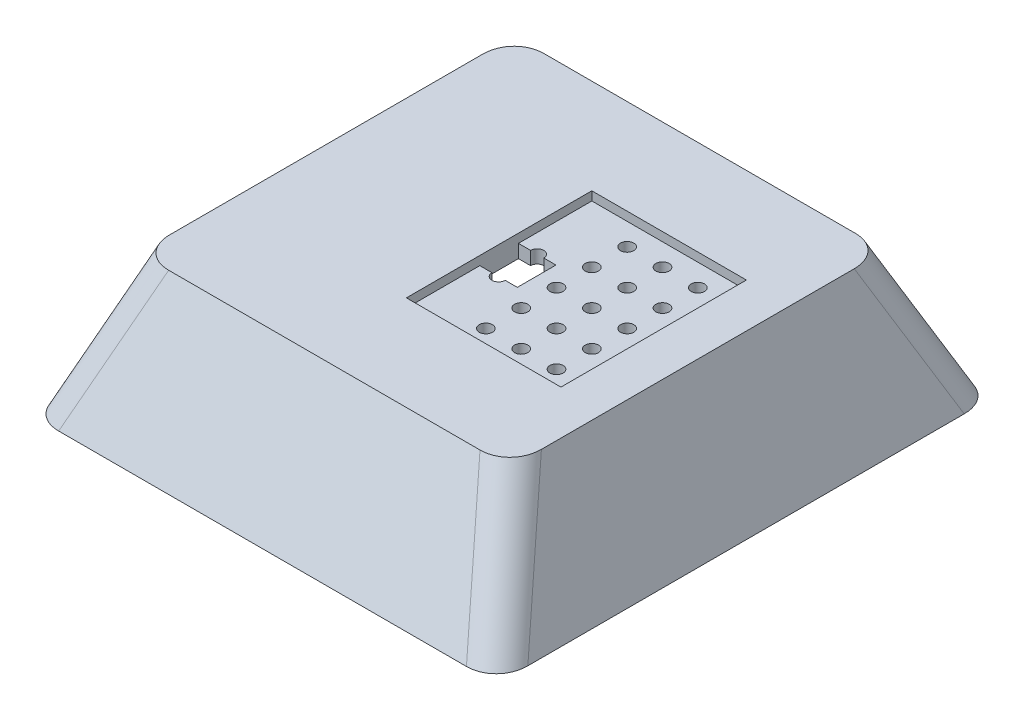
SolidWorks part; units mm, degrees
ref_plane "Front Plane" through (0, 0, 0) normal (0, 0, 1) x (1, 0, 0)
ref_plane "Top Plane" through (0, 0, 0) normal (0, 1, 0) x (1, 0, 0)
ref_plane "Right Plane" through (0, 0, 0) normal (1, 0, 0) x (0, 0, -1)
sketch "Master_Geometry" plane through (0, 0, 0) normal (0, 0, 1) x (1, 0, 0)
  line L0 (-48, -3.5) -> (-53, -3.5)
  line L1 (-47.5, -3.5) -> (47.5, -3.5) construction
  line L2 (-47.5, -3.5) -> (-47.5, 3.5) construction
  line L3 (-47.5, 3.5) -> (47.5, 3.5) construction
  line L4 (47.5, -3.5) -> (47.5, 3.5) construction
  line L5 (-47.5, -3.5) -> (47.5, 3.5) construction
  line L6 (-47.5, 3.5) -> (47.5, -3.5) construction
  line L7 (-53, -3.5) -> (-42.0809, 26.5)
  line L8 (-42.0809, 26.5) -> (42.0809, 26.5)
  line L13 (42.0809, 26.5) -> (53, -3.5)
  line L14 (53, -3.5) -> (48, -3.5)
  line L15 (48, -3.5) -> (48, 4)
  line L16 (48, 4) -> (38, 4)
  line L17 (38, 4) -> (38, 21.5)
  line L18 (38, 21.5) -> (-38, 21.5)
  line L19 (-38, 21.5) -> (-38, 4)
  line L20 (-38, 4) -> (-48, 4)
  line L21 (-48, 4) -> (-48, -3.5)
  point P0 (0, 0)
  dimension "D1" = 95
  dimension "D2" = 7
  dimension "D3" = 18
  dimension "D4" = 0.5
  dimension "D5" = 0.5
  dimension "D6" = 10
  dimension "D7" = 0.5
  dimension "D8" = 0.5
  dimension "D9" = 10
  dimension "D11" = 70
  dimension "D12" = 70
  dimension "D19" = 5
  dimension "D20" = 5
  dimension "D10" = 5
extrude "Top_Enclosure" add sketch "Master_Geometry" along normal blind 65
sketch "Sketch2" plane through (0, 0, 65) normal (0, 0, 1) x (1, 0, 0)
  line L0 (-42.0809, 26.5) -> (42.0809, 26.5)
  line L1 (42.0809, 26.5) -> (53, -3.5)
  line L2 (53, -3.5) -> (-53, -3.5)
  line L3 (-53, -3.5) -> (-42.0809, 26.5)
extrude "Top_Extra" add sketch "Sketch2" along normal blind 10
ref_plane "Plane_Symm" through (0, 0, 32.5) normal (0, 0, -1) x (-1, 0, 0)
mirror "Mirror1" about plane through (0, 0, 32.5) normal (0, 0, -1) of "Top_Extra"
sketch "Sketch3" plane through (0, 26.5, 0) normal (0, 1, 0) x (1, 0, 0)
  line L0 (13.75, -32.5) -> (-13.75, -32.5) construction
  line L1 (-2.9191, -53.5) -> (32.0809, -53.5)
  line L2 (-2.9191, -53.5) -> (-2.9191, -11.5)
  line L3 (-2.9191, -11.5) -> (32.0809, -11.5)
  line L4 (32.0809, -53.5) -> (32.0809, -11.5)
  line L5 (-2.9191, -53.5) -> (32.0809, -11.5) construction
  line L6 (-2.9191, -11.5) -> (32.0809, -53.5) construction
  line L7 (42.0809, -75) -> (42.0809, 10) construction
  point P0 (14.5809, -32.5)
  dimension "D1" = 35
  dimension "D2" = 42
  dimension "D3" = 10
extrude "Solar_Cell_Slot" cut sketch "Sketch3" against normal blind 2
sketch "Sketch4" plane through (0, 24.5, 0) normal (0, 1, 0) x (1, 0, 0)
  line L0 (2.8309, -28.125) -> (5.5809, -28.125)
  line L1 (-2.9191, -32.5) -> (32.0809, -32.5) construction
  line L2 (13.75, -32.5) -> (-13.75, -32.5) construction
  line L3 (-2.9191, -11.5) -> (-2.9191, -53.5) construction
  line L4 (32.0809, -53.5) -> (32.0809, -11.5) construction
  line L5 (-2.9191, -36.875) -> (-0.1691, -36.875)
  line L6 (-2.9191, -36.875) -> (-2.9191, -28.125)
  line L7 (-2.9191, -28.125) -> (-0.1691, -28.125)
  line L8 (5.5809, -36.875) -> (5.5809, -28.125)
  line L9 (-2.9191, -36.875) -> (5.5809, -28.125) construction
  line L10 (-2.9191, -28.125) -> (5.5809, -36.875) construction
  line L11 (2.8309, -36.875) -> (5.5809, -36.875)
  arc A0 (2.8309, -28.125) -> (-0.1691, -28.125) centre (1.3309, -28.125) ccw
  arc A1 (-0.1691, -36.875) -> (2.8309, -36.875) centre (1.3309, -36.875) ccw
  circle A2 centre (10.0809, -32.5) radius 1.5
  circle A3 centre (18.0809, -32.5) radius 1.5
  circle A4 centre (26.0809, -32.5) radius 1.5
  circle A5 centre (10.0809, -40.5) radius 1.5
  circle A6 centre (18.0809, -40.5) radius 1.5
  circle A7 centre (26.0809, -40.5) radius 1.5
  circle A8 centre (10.0809, -48.5) radius 1.5
  circle A9 centre (18.0809, -48.5) radius 1.5
  circle A10 centre (26.0809, -48.5) radius 1.5
  circle A11 centre (10.0809, -24.5) radius 1.5
  circle A12 centre (18.0809, -24.5) radius 1.5
  circle A13 centre (26.0809, -24.5) radius 1.5
  circle A14 centre (10.0809, -16.5) radius 1.5
  circle A15 centre (18.0809, -16.5) radius 1.5
  circle A16 centre (26.0809, -16.5) radius 1.5
  point P6 (1.3309, -32.5)
  dimension "D2" = 3
  dimension "D3" = 3
  dimension "D9" = 3
  dimension "D10" = 3
  dimension "D11" = 3
  dimension "D1" = 8.75
  dimension "D4" = 4.25
  dimension "D5" = 8.5
  dimension "D6" = 8.75
  dimension "D7" = 8
  dimension "D8" = 8
  dimension "D12" = 6
  dimension "D15" = 8
  dimension "D16" = 8
  dimension "D13" = 3
  dimension "D14" = 3
extrude "Solar_Cell_Holes" cut sketch "Sketch4" against normal through all
sketch "Sketch5" plane through (0, 0, 0) normal (1, 0, 0) x (0, 0, -1)
  line L0 (-75, 26.5) -> (-75, -3.5)
  line L1 (-75, -3.5) -> (-88.9892, -3.5)
  line L2 (-88.9892, -3.5) -> (-75, 26.5)
  dimension "D1" = 65
extrude "Boss-Extrude1" add sketch "Sketch5" along normal up to surface (53 mm away)
sketch "Sketch6" plane through (0, 0, 0) normal (-1, 0, 0) x (0, 0, 1)
  line L0 (75, 26.5) -> (88.9892, -3.5)
  line L1 (88.9892, -3.5) -> (75, -3.5)
  line L2 (75, -3.5) -> (75, 26.5)
extrude "Boss-Extrude2" add sketch "Sketch6" along normal up to surface (42.0809 mm away) contours L2 L0 L1
mirror "Mirror3" about plane through (0, 0, 32.5) normal (0, 0, -1) of "Boss-Extrude2", "Boss-Extrude1"
fillet "Fillet1" radius 7.5 4 edges at (47.5404, 11.5, 81.9946) (-47.5404, 11.5, 81.9946) (47.5404, 11.5, -16.9946) (-47.5404, 11.5, -16.9946)
hole_wizard "CBORE for M5 Hex Head Bolt1" positions "Sketch7" profile "Sketch8" counterbore size "M5" standard "ANSI Metric"
sketch "Sketch7" plane through (0, -3.5, 0) normal (0, -1, 0) x (-1, 0, 0)
  line L0 (-46.1723, -88.9892) -> (46.1723, -88.9892) construction
  line L1 (-46.1723, 23.9892) -> (46.1723, 23.9892) construction
  point P0 (35, -76.9892)
  point P2 (0, -76.9892)
  point P4 (-35, -76.9892)
  point P6 (-35, 11.9892)
  point P8 (0, 11.9892)
  point P10 (35, 11.9892)
  dimension "D1" = 35
  dimension "D2" = 35
  dimension "D3" = 12
  dimension "D4" = 12
sketch "Sketch8" plane through (-35, -3.5, 76.9892) normal (1, 0, 0) x (0, 0, -1)
  line L0 (0, 0) -> (0, 10)
  line L1 (0, 10) -> (2.65, 10)
  line L2 (2.65, 10) -> (2.65, 5)
  line L3 (2.65, 5) -> (3.5, 5)
  line L4 (3.5, 5) -> (3.5, 0)
  line L5 (3.5, 0) -> (0, 0)
  line L10 (0, 10) -> (-2.65, 10) construction
  line L11 (0, -6.35) -> (0, 107.95) construction
  dimension "Hole Dia." = 5.3
  dimension "Hole Depth" = 10
  dimension "C'Bore Dia." = 7
  dimension "C'Bore Depth" = 5
  dimension "Drill Angle" = 180
equation "\"rel_tol\"= 0.5mm"
equation "\"dist_pcb_top\"= 18mm"
equation "\"enclosure_angle\"= 70deg"
equation "\"solar_cell_x\"= 42mm"
equation "\"solar_cell_y\"= 35mm"
equation "\"solar_cell_z\"= 2mm"
equation "\"top_extra\"= 10mm"
equation "\"top_thickness\"= 5mm"
equation "\"top_extra_bottom\"= 5mm"
equation "\"solar_cell_pos\"= 35mm"
equation "\"bottom_overall_x\"= 95mm"
equation "\"bottom_overall_y\"= 7mm"
equation "\"D1@Master_Geometry\" = \"bottom_overall_x\""
equation "\"D3@Master_Geometry\" = \"dist_pcb_top\""
equation "\"D4@Master_Geometry\" = \"rel_tol\""
equation "\"D5@Master_Geometry\" = \"rel_tol\""
equation "\"D6@Master_Geometry\" = \"top_extra\""
equation "\"D7@Master_Geometry\" = \"rel_tol\""
equation "\"D8@Master_Geometry\" = \"rel_tol\""
equation "\"D9@Master_Geometry\" = \"top_extra\""
equation "\"D11@Master_Geometry\" = \"enclosure_angle\""
equation "\"D12@Master_Geometry\" = \"enclosure_angle\""
equation "\"D19@Master_Geometry\" = \"top_extra_bottom\""
equation "\"D20@Master_Geometry\" = \"top_extra_bottom\""
equation "\"pcb_length\"= 90mm"
equation "\"pcb_width\"= 65mm"
equation "\"D1@Top_Enclosure\"=65mm"
equation "\"D10@Master_Geometry\" = \"top_thickness\""
equation "\"top_extra_outside\"= 10mm"
equation "\"D1@Top_Extra\" = \"top_extra_outside\""
equation "\"D1@Sketch3\"=\"solar_cell_y\""
equation "\"D2@Sketch3\"=\"solar_cell_x\""
equation "\"D1@Solar_Cell_Slot\" = \"solar_cell_z\""
equation "\"flatter_region\"= 65deg"
equation "\"D1@Sketch5\"=\"flatter_region\""
